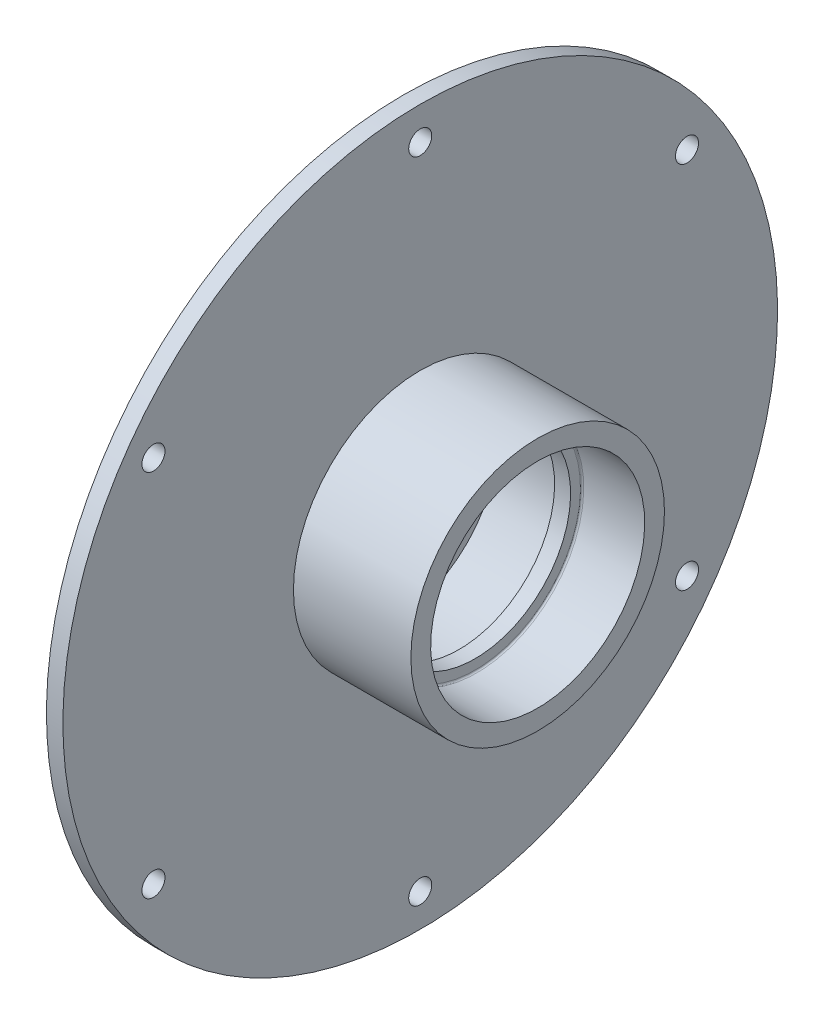
SolidWorks part; units mm, degrees
ref_plane "Front Plane" through (0, 0, 0) normal (0, 0, 1) x (1, 0, 0)
ref_plane "Top Plane" through (0, 0, 0) normal (0, 1, 0) x (1, 0, 0)
ref_plane "Right Plane" through (0, 0, 0) normal (1, 0, 0) x (0, 0, -1)
sketch "Sketch1" plane through (0, 0, 0) normal (0, 0, 1) x (1, 0, 0)
  line L0 (131.4815, 0) -> (-131.4815, 0) construction
  line L1 (89, 65) -> (51, 65)
  line L2 (51, 65) -> (51, 58)
  line L3 (51, 58) -> (41.3, 58)
  line L4 (41.3, 58) -> (41.3, 65)
  line L5 (41.3, 65) -> (0, 65)
  line L8 (7.686, 129.5) -> (7.686, 217)
  line L9 (7.686, 217) -> (17.686, 217)
  line L11 (17.686, 217) -> (17.686, 77)
  line L12 (17.686, 77) -> (89, 77)
  line L13 (89, 77) -> (89, 65)
  line L14 (0, 65) -> (0, 55)
  line L15 (0, 55) -> (-5, 55)
  line L16 (-5, 55) -> (-5, 59.5)
  line L17 (-5, 59.5) -> (-15, 59.5)
  line L18 (-17, 61.5) -> (-17, 109.5)
  line L19 (7.686, 129.5) -> (3, 129.5)
  line L20 (-29.2027, 42.5) -> (69.8517, 42.5) construction
  arc A0 (-17, 109.5) -> (3, 129.5) centre (3, 109.5) cw
  arc A1 (-15, 59.5) -> (-17, 61.5) centre (-15, 61.5) cw
  point P4 (0, 0)
  point P26 (-17, 59.5)
  point P27 (0, 0)
  dimension "D13" = 20
  dimension "D15" = 2
  dimension "D1" = 9.7
  dimension "D2" = 7
  dimension "D3" = 65
  dimension "D4" = 38
  dimension "D5" = 12
  dimension "D6" = 59.5
  dimension "D7" = 140
  dimension "D8" = 10
  dimension "D9" = 55
  dimension "D10" = 12
  dimension "D11" = 5
  dimension "D12" = 42.5
  dimension "D14" = 50
  dimension "D16" = 41.3
revolve "Revolve1" add sketch "Sketch1" angle 360 about L0
fillet "Fillet1" radius 1 2 edges at (51, 65, 0) (41.3, 65, 0)
sketch "Sketch2" plane through (7.686, 0, 0) normal (-1, 0, 0) x (0, 0, 1)
  circle A0 centre (0, 0) radius 197 construction
  dimension "D1" = 394
hole_wizard "M16x2.0 Tapped Hole1" positions "Sketch3" profile "Sketch4" tap size "M16x2.0" standard "ANSI Metric"
sketch "Sketch3" plane through (7.686, 0, 0) normal (-1, 0, 0) x (0, 0, 1)
  circle A0 centre (0, 0) radius 197 construction
  point P0 (0, 197)
  point P4 (0, -197)
  point P6 (162, -112.0937)
  point P8 (-162, -112.0937)
  point P10 (-162, 112.0937)
  point P12 (162, 112.0937)
  dimension "D1" = 162
  dimension "D2" = 162
  dimension "D3" = 162
  dimension "D4" = 162
sketch "Sketch4" plane through (7.686, 197, 0) normal (0, 1, 0) x (0, 0, 1)
  line L0 (0, 0) -> (0, 42.206)
  line L1 (0, 42.206) -> (7, 38)
  line L2 (7, 38) -> (7, 0)
  line L5 (7, 0) -> (0, 0)
  line L10 (0, 42.206) -> (-7, 38) construction
  line L11 (0, -6.35) -> (0, 107.95) construction
  dimension "Tap Drill Dia." = 14
  dimension "Tap Drill Depth" = 38
  dimension "Drill Angle" = 118
cosmetic thread "Hole Thread1" parameters "D1"=32, "D2"=16
cosmetic thread "Hole Thread2" parameters "D1"=32, "D2"=16
cosmetic thread "Hole Thread3" parameters "D1"=32, "D2"=16
cosmetic thread "Hole Thread4" parameters "D1"=32, "D2"=16
cosmetic thread "Hole Thread5" parameters "D1"=32, "D2"=16
cosmetic thread "Hole Thread6" parameters "D1"=32, "D2"=16
